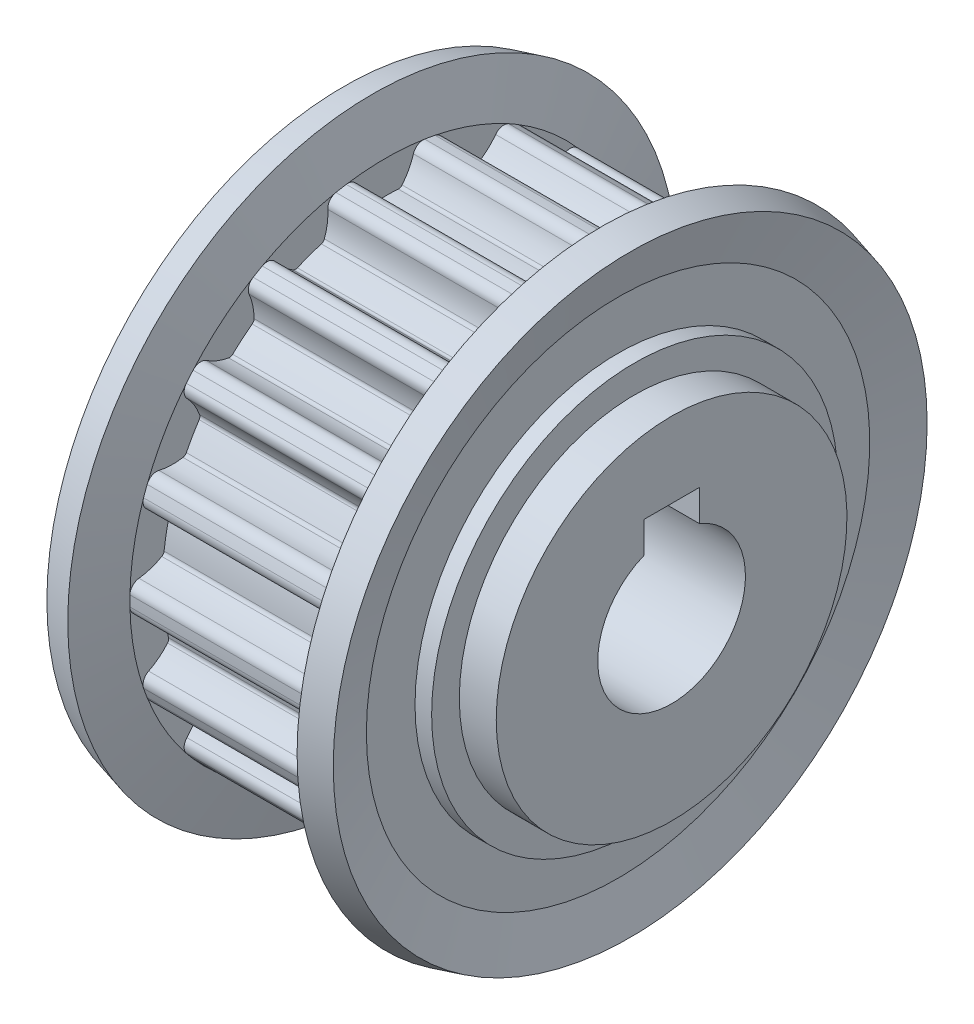
SolidWorks part; units mm, degrees
material "AISI 1045 강, 냉간압연"
ref_plane "정면" through (0, 0, 0) normal (0, 0, 1) x (1, 0, 0)
ref_plane "윗면" through (0, 0, 0) normal (0, 1, 0) x (1, 0, 0)
ref_plane "우측면" through (0, 0, 0) normal (1, 0, 0) x (0, 0, -1)
ref_plane "평면1" through (0, 0, 0) normal (0, 0, 1) x (1, 0, 0)
sketch "스케치1" plane through (0, 0, 0) normal (0, 0, 1) x (1, 0, 0)
  line L0 (0, 0) -> (0, 11)
  line L1 (0, 11) -> (0.9, 11)
  line L2 (0.9, 11) -> (0.9, 13.6344)
  line L3 (0.9, 13.6344) -> (0.2431, 16.0859)
  line L4 (0.2431, 16.0859) -> (1.7886, 16.5)
  line L5 (1.7886, 16.5) -> (2.5, 13.845)
  line L6 (2.5, 13.845) -> (13.5, 13.845)
  line L7 (13.5, 13.845) -> (14.2114, 16.5)
  line L8 (14.2114, 16.5) -> (15.7569, 16.0859)
  line L9 (15.7569, 16.0859) -> (15.1, 13.6344)
  line L10 (15.1, 13.6344) -> (15.1, 11)
  line L11 (15.1, 11) -> (16, 11)
  line L12 (16, 11) -> (16, 9.5)
  line L13 (16, 9.5) -> (25, 9.5)
  line L14 (25, 9.5) -> (25, 0)
  line L15 (25, 0) -> (0, 0)
  line L16 (25, 0) -> (0, 0) construction
revolve "회전1" add sketch "스케치1" angle 360 about L16
ref_plane "평면2" through (0, 0, 0) normal (0, 0, 1) x (1, 0, 0)
sketch "스케치2" plane through (0, 0, 0) normal (0, 0, 1) x (1, 0, 0)
  line L0 (0, 0) -> (0, 4)
  line L1 (0, 4) -> (25, 4)
  line L2 (25, 4) -> (25, 0)
  line L3 (25, 0) -> (0, 0)
  line L4 (25, 0) -> (0, 0) construction
revolve "컷-회전1" cut sketch "스케치2" angle 360 about L4
ref_plane "평면3" through (2.5, 0, 0) normal (1, 0, 0) x (0, 0, -1)
sketch "스케치3" plane through (2.5, 0, 0) normal (1, 0, 0) x (0, 0, -1)
  line L0 (2.1243, 13.6811) -> (2.1243, 14.1666)
  line L1 (-2.1243, 14.1666) -> (-2.1243, 13.6811)
  arc A0 (-2.1243, 13.6811) -> (-1.5129, 13.295) centre (-2.0399, 13.1376) cw
  arc A1 (-1.5129, 13.295) -> (-0.8988, 12.1454) centre (1.625, 14.2325) ccw
  arc A2 (-0.8988, 12.1454) -> (-0.6918, 12.0552) centre (-0.7062, 12.3048) ccw
  arc A3 (-0.6918, 12.0552) -> (0.6918, 12.0552) centre (0, 0) cw
  arc A4 (0.6918, 12.0552) -> (0.8988, 12.1454) centre (0.7062, 12.3048) ccw
  arc A5 (0.8988, 12.1454) -> (1.5129, 13.295) centre (-1.625, 14.2325) ccw
  arc A6 (1.5129, 13.295) -> (2.1243, 13.6811) centre (2.0399, 13.1376) cw
  arc A7 (2.1243, 14.1666) -> (-2.1243, 14.1666) centre (0, 0) ccw
extrude "컷-돌출1" cut sketch "스케치3" along normal blind 11
ref_plane "평면4" through (2.5, 0, 0) normal (1, 0, 0) x (0, 0, -1)
sketch "스케치4" plane through (2.5, 0, 0) normal (1, 0, 0) x (0, 0, -1)
  line L0 (6.6754, 12.1294) -> (6.8415, 12.5857)
  line L1 (2.8491, 14.0388) -> (2.683, 13.5825)
  arc A0 (2.683, 13.5825) -> (3.1255, 13.0107) centre (2.5764, 13.043) cw
  arc A1 (3.1255, 13.0107) -> (3.3094, 11.7204) centre (6.3948, 12.8184) ccw
  arc A2 (3.3094, 11.7204) -> (3.473, 11.5648) centre (3.5449, 11.8042) ccw
  arc A3 (3.473, 11.5648) -> (4.7732, 11.0915) centre (0, 0) cw
  arc A4 (4.7732, 11.0915) -> (4.9986, 11.1056) centre (4.872, 11.3212) ccw
  arc A5 (4.9986, 11.1056) -> (5.9689, 11.9758) centre (3.3408, 13.93) ccw
  arc A6 (5.9689, 11.9758) -> (6.6754, 12.1294) centre (6.4102, 11.6476) cw
  arc A7 (6.8415, 12.5857) -> (2.8491, 14.0388) centre (0, 0) ccw
extrude "컷-돌출2" cut sketch "스케치4" along normal blind 11
ref_plane "평면5" through (2.5, 0, 0) normal (1, 0, 0) x (0, 0, -1)
sketch "스케치5" plane through (2.5, 0, 0) normal (1, 0, 0) x (0, 0, -1)
  line L0 (10.4213, 9.1148) -> (10.7334, 9.4868)
  line L1 (7.4788, 12.2177) -> (7.1667, 11.8458)
  arc A0 (7.1667, 11.8458) -> (7.3869, 11.1571) centre (6.882, 11.3752) cw
  arc A1 (7.3869, 11.1571) -> (7.1184, 9.8817) centre (10.3933, 9.8582) ccw
  arc A2 (7.1184, 9.8817) -> (7.2189, 9.6795) centre (7.3684, 9.8799) ccw
  arc A3 (7.2189, 9.6795) -> (8.2789, 8.7901) centre (0, 0) cw
  arc A4 (8.2789, 8.7901) -> (8.4955, 8.7262) centre (8.4503, 8.9721) ccw
  arc A5 (8.4955, 8.7262) -> (9.7049, 9.2121) centre (7.9037, 11.9473) ccw
  arc A6 (9.7049, 9.2121) -> (10.4213, 9.1148) centre (10.0073, 8.7527) cw
  arc A7 (10.7334, 9.4868) -> (7.4788, 12.2177) centre (0, 0) ccw
extrude "컷-돌출3" cut sketch "스케치5" along normal blind 11
ref_plane "평면6" through (2.5, 0, 0) normal (1, 0, 0) x (0, 0, -1)
sketch "스케치6" plane through (2.5, 0, 0) normal (1, 0, 0) x (0, 0, -1)
  line L0 (12.9103, 5.0008) -> (13.3308, 5.2436)
  line L1 (11.2065, 8.923) -> (10.786, 8.6802)
  arc A0 (10.786, 8.6802) -> (10.7573, 7.9578) centre (10.3575, 8.3354) cw
  arc A1 (10.7573, 7.9578) -> (10.0688, 6.8511) centre (13.1382, 5.709) ccw
  arc A2 (10.0688, 6.8511) -> (10.0942, 6.6267) centre (10.3032, 6.7639) ccw
  arc A3 (10.0942, 6.6267) -> (10.786, 5.4284) centre (0, 0) cw
  arc A4 (10.786, 5.4284) -> (10.9677, 5.2943) centre (11.0093, 5.5408) ccw
  arc A5 (10.9677, 5.2943) -> (12.2703, 5.3373) centre (11.5132, 8.5236) ccw
  arc A6 (12.2703, 5.3373) -> (12.9103, 5.0008) centre (12.3974, 4.8022) cw
  arc A7 (13.3308, 5.2436) -> (11.2065, 8.923) centre (0, 0) ccw
extrude "컷-돌출4" cut sketch "스케치6" along normal blind 11
ref_plane "평면7" through (2.5, 0, 0) normal (1, 0, 0) x (0, 0, -1)
sketch "스케치7" plane through (2.5, 0, 0) normal (1, 0, 0) x (0, 0, -1)
  line L0 (13.8421, 0.2836) -> (14.3203, 0.368)
  line L1 (13.5825, 4.552) -> (13.1043, 4.4677)
  arc A0 (13.1043, 4.4677) -> (12.8303, 3.7986) centre (12.5838, 4.2902) cw
  arc A1 (12.8303, 3.7986) -> (11.8048, 2.9942) centre (14.2985, 0.8711) ccw
  arc A2 (11.8048, 2.9942) -> (11.7519, 2.7747) centre (11.9952, 2.8321) ccw
  arc A3 (11.7519, 2.7747) -> (11.9922, 1.412) centre (0, 0) cw
  arc A4 (11.9922, 1.412) -> (12.117, 1.2239) centre (12.2404, 1.4413) ccw
  arc A5 (12.117, 1.2239) -> (13.3558, 0.8187) centre (13.7341, 4.0718) ccw
  arc A6 (13.3558, 0.8187) -> (13.8421, 0.2836) centre (13.2922, 0.2724) cw
  arc A7 (14.3203, 0.368) -> (13.5825, 4.552) centre (0, 0) ccw
extrude "컷-돌출5" cut sketch "스케치7" along normal blind 11
ref_plane "평면8" through (2.5, 0, 0) normal (1, 0, 0) x (0, 0, -1)
sketch "스케치8" plane through (2.5, 0, 0) normal (1, 0, 0) x (0, 0, -1)
  line L0 (13.1043, -4.4677) -> (13.5825, -4.552)
  line L1 (14.3203, -0.368) -> (13.8421, -0.2836)
  arc A0 (13.8421, -0.2836) -> (13.3558, -0.8187) centre (13.2922, -0.2724) cw
  arc A1 (13.3558, -0.8187) -> (12.117, -1.2239) centre (13.7341, -4.0718) ccw
  arc A2 (12.117, -1.2239) -> (11.9922, -1.412) centre (12.2404, -1.4413) ccw
  arc A3 (11.9922, -1.412) -> (11.7519, -2.7747) centre (0, 0) cw
  arc A4 (11.7519, -2.7747) -> (11.8048, -2.9942) centre (11.9952, -2.8321) ccw
  arc A5 (11.8048, -2.9942) -> (12.8303, -3.7986) centre (14.2985, -0.8711) ccw
  arc A6 (12.8303, -3.7986) -> (13.1043, -4.4677) centre (12.5838, -4.2902) cw
  arc A7 (13.5825, -4.552) -> (14.3203, -0.368) centre (0, 0) ccw
extrude "컷-돌출6" cut sketch "스케치8" along normal blind 11
ref_plane "평면9" through (2.5, 0, 0) normal (1, 0, 0) x (0, 0, -1)
sketch "스케치9" plane through (2.5, 0, 0) normal (1, 0, 0) x (0, 0, -1)
  line L0 (10.786, -8.6802) -> (11.2065, -8.923)
  line L1 (13.3308, -5.2436) -> (12.9103, -5.0008)
  arc A0 (12.9103, -5.0008) -> (12.2703, -5.3373) centre (12.3974, -4.8022) cw
  arc A1 (12.2703, -5.3373) -> (10.9677, -5.2943) centre (11.5132, -8.5236) ccw
  arc A2 (10.9677, -5.2943) -> (10.786, -5.4284) centre (11.0093, -5.5408) ccw
  arc A3 (10.786, -5.4284) -> (10.0942, -6.6267) centre (0, 0) cw
  arc A4 (10.0942, -6.6267) -> (10.0688, -6.8511) centre (10.3032, -6.7639) ccw
  arc A5 (10.0688, -6.8511) -> (10.7573, -7.9578) centre (13.1382, -5.709) ccw
  arc A6 (10.7573, -7.9578) -> (10.786, -8.6802) centre (10.3575, -8.3354) cw
  arc A7 (11.2065, -8.923) -> (13.3308, -5.2436) centre (0, 0) ccw
extrude "컷-돌출7" cut sketch "스케치9" along normal blind 11
ref_plane "평면10" through (2.5, 0, 0) normal (1, 0, 0) x (0, 0, -1)
sketch "스케치10" plane through (2.5, 0, 0) normal (1, 0, 0) x (0, 0, -1)
  line L0 (7.1667, -11.8458) -> (7.4788, -12.2177)
  line L1 (10.7334, -9.4868) -> (10.4213, -9.1148)
  arc A0 (10.4213, -9.1148) -> (9.7049, -9.2121) centre (10.0073, -8.7527) cw
  arc A1 (9.7049, -9.2121) -> (8.4955, -8.7262) centre (7.9037, -11.9473) ccw
  arc A2 (8.4955, -8.7262) -> (8.2789, -8.7901) centre (8.4503, -8.9721) ccw
  arc A3 (8.2789, -8.7901) -> (7.2189, -9.6795) centre (0, 0) cw
  arc A4 (7.2189, -9.6795) -> (7.1184, -9.8817) centre (7.3684, -9.8799) ccw
  arc A5 (7.1184, -9.8817) -> (7.3869, -11.1571) centre (10.3933, -9.8582) ccw
  arc A6 (7.3869, -11.1571) -> (7.1667, -11.8458) centre (6.882, -11.3752) cw
  arc A7 (7.4788, -12.2177) -> (10.7334, -9.4868) centre (0, 0) ccw
extrude "컷-돌출8" cut sketch "스케치10" along normal blind 11
ref_plane "평면11" through (2.5, 0, 0) normal (1, 0, 0) x (0, 0, -1)
sketch "스케치11" plane through (2.5, 0, 0) normal (1, 0, 0) x (0, 0, -1)
  line L0 (2.683, -13.5825) -> (2.8491, -14.0388)
  line L1 (6.8415, -12.5857) -> (6.6754, -12.1294)
  arc A0 (6.6754, -12.1294) -> (5.9689, -11.9758) centre (6.4102, -11.6476) cw
  arc A1 (5.9689, -11.9758) -> (4.9986, -11.1056) centre (3.3408, -13.93) ccw
  arc A2 (4.9986, -11.1056) -> (4.7732, -11.0915) centre (4.872, -11.3212) ccw
  arc A3 (4.7732, -11.0915) -> (3.473, -11.5648) centre (0, 0) cw
  arc A4 (3.473, -11.5648) -> (3.3094, -11.7204) centre (3.5449, -11.8042) ccw
  arc A5 (3.3094, -11.7204) -> (3.1255, -13.0107) centre (6.3948, -12.8184) ccw
  arc A6 (3.1255, -13.0107) -> (2.683, -13.5825) centre (2.5764, -13.043) cw
  arc A7 (2.8491, -14.0388) -> (6.8415, -12.5857) centre (0, 0) ccw
extrude "컷-돌출9" cut sketch "스케치11" along normal blind 11
ref_plane "평면12" through (2.5, 0, 0) normal (1, 0, 0) x (0, 0, -1)
sketch "스케치12" plane through (2.5, 0, 0) normal (1, 0, 0) x (0, 0, -1)
  line L0 (-2.1243, -13.6811) -> (-2.1243, -14.1666)
  line L1 (2.1243, -14.1666) -> (2.1243, -13.6811)
  arc A0 (2.1243, -13.6811) -> (1.5129, -13.295) centre (2.0399, -13.1376) cw
  arc A1 (1.5129, -13.295) -> (0.8988, -12.1454) centre (-1.625, -14.2325) ccw
  arc A2 (0.8988, -12.1454) -> (0.6918, -12.0552) centre (0.7062, -12.3048) ccw
  arc A3 (0.6918, -12.0552) -> (-0.6918, -12.0552) centre (0, 0) cw
  arc A4 (-0.6918, -12.0552) -> (-0.8988, -12.1454) centre (-0.7062, -12.3048) ccw
  arc A5 (-0.8988, -12.1454) -> (-1.5129, -13.295) centre (1.625, -14.2325) ccw
  arc A6 (-1.5129, -13.295) -> (-2.1243, -13.6811) centre (-2.0399, -13.1376) cw
  arc A7 (-2.1243, -14.1666) -> (2.1243, -14.1666) centre (0, 0) ccw
extrude "컷-돌출10" cut sketch "스케치12" along normal blind 11
ref_plane "평면13" through (2.5, 0, 0) normal (1, 0, 0) x (0, 0, -1)
sketch "스케치13" plane through (2.5, 0, 0) normal (1, 0, 0) x (0, 0, -1)
  line L0 (-6.6754, -12.1294) -> (-6.8415, -12.5857)
  line L1 (-2.8491, -14.0388) -> (-2.683, -13.5825)
  arc A0 (-2.683, -13.5825) -> (-3.1255, -13.0107) centre (-2.5764, -13.043) cw
  arc A1 (-3.1255, -13.0107) -> (-3.3094, -11.7204) centre (-6.3948, -12.8184) ccw
  arc A2 (-3.3094, -11.7204) -> (-3.473, -11.5648) centre (-3.5449, -11.8042) ccw
  arc A3 (-3.473, -11.5648) -> (-4.7732, -11.0915) centre (0, 0) cw
  arc A4 (-4.7732, -11.0915) -> (-4.9986, -11.1056) centre (-4.872, -11.3212) ccw
  arc A5 (-4.9986, -11.1056) -> (-5.9689, -11.9758) centre (-3.3408, -13.93) ccw
  arc A6 (-5.9689, -11.9758) -> (-6.6754, -12.1294) centre (-6.4102, -11.6476) cw
  arc A7 (-6.8415, -12.5857) -> (-2.8491, -14.0388) centre (0, 0) ccw
extrude "컷-돌출11" cut sketch "스케치13" along normal blind 11
ref_plane "평면14" through (2.5, 0, 0) normal (1, 0, 0) x (0, 0, -1)
sketch "스케치14" plane through (2.5, 0, 0) normal (1, 0, 0) x (0, 0, -1)
  line L0 (-10.4213, -9.1148) -> (-10.7334, -9.4868)
  line L1 (-7.4788, -12.2177) -> (-7.1667, -11.8458)
  arc A0 (-7.1667, -11.8458) -> (-7.3869, -11.1571) centre (-6.882, -11.3752) cw
  arc A1 (-7.3869, -11.1571) -> (-7.1184, -9.8817) centre (-10.3933, -9.8582) ccw
  arc A2 (-7.1184, -9.8817) -> (-7.2189, -9.6795) centre (-7.3684, -9.8799) ccw
  arc A3 (-7.2189, -9.6795) -> (-8.2789, -8.7901) centre (0, 0) cw
  arc A4 (-8.2789, -8.7901) -> (-8.4955, -8.7262) centre (-8.4503, -8.9721) ccw
  arc A5 (-8.4955, -8.7262) -> (-9.7049, -9.2121) centre (-7.9037, -11.9473) ccw
  arc A6 (-9.7049, -9.2121) -> (-10.4213, -9.1148) centre (-10.0073, -8.7527) cw
  arc A7 (-10.7334, -9.4868) -> (-7.4788, -12.2177) centre (0, 0) ccw
extrude "컷-돌출12" cut sketch "스케치14" along normal blind 11
ref_plane "평면15" through (2.5, 0, 0) normal (1, 0, 0) x (0, 0, -1)
sketch "스케치15" plane through (2.5, 0, 0) normal (1, 0, 0) x (0, 0, -1)
  line L0 (-12.9103, -5.0008) -> (-13.3308, -5.2436)
  line L1 (-11.2065, -8.923) -> (-10.786, -8.6802)
  arc A0 (-10.786, -8.6802) -> (-10.7573, -7.9578) centre (-10.3575, -8.3354) cw
  arc A1 (-10.7573, -7.9578) -> (-10.0688, -6.8511) centre (-13.1382, -5.709) ccw
  arc A2 (-10.0688, -6.8511) -> (-10.0942, -6.6267) centre (-10.3032, -6.7639) ccw
  arc A3 (-10.0942, -6.6267) -> (-10.786, -5.4284) centre (0, 0) cw
  arc A4 (-10.786, -5.4284) -> (-10.9677, -5.2943) centre (-11.0093, -5.5408) ccw
  arc A5 (-10.9677, -5.2943) -> (-12.2703, -5.3373) centre (-11.5132, -8.5236) ccw
  arc A6 (-12.2703, -5.3373) -> (-12.9103, -5.0008) centre (-12.3974, -4.8022) cw
  arc A7 (-13.3308, -5.2436) -> (-11.2065, -8.923) centre (0, 0) ccw
extrude "컷-돌출13" cut sketch "스케치15" along normal blind 11
ref_plane "평면16" through (2.5, 0, 0) normal (1, 0, 0) x (0, 0, -1)
sketch "스케치16" plane through (2.5, 0, 0) normal (1, 0, 0) x (0, 0, -1)
  line L0 (-13.8421, -0.2836) -> (-14.3203, -0.368)
  line L1 (-13.5825, -4.552) -> (-13.1043, -4.4677)
  arc A0 (-13.1043, -4.4677) -> (-12.8303, -3.7986) centre (-12.5838, -4.2902) cw
  arc A1 (-12.8303, -3.7986) -> (-11.8048, -2.9942) centre (-14.2985, -0.8711) ccw
  arc A2 (-11.8048, -2.9942) -> (-11.7519, -2.7747) centre (-11.9952, -2.8321) ccw
  arc A3 (-11.7519, -2.7747) -> (-11.9922, -1.412) centre (0, 0) cw
  arc A4 (-11.9922, -1.412) -> (-12.117, -1.2239) centre (-12.2404, -1.4413) ccw
  arc A5 (-12.117, -1.2239) -> (-13.3558, -0.8187) centre (-13.7341, -4.0718) ccw
  arc A6 (-13.3558, -0.8187) -> (-13.8421, -0.2836) centre (-13.2922, -0.2724) cw
  arc A7 (-14.3203, -0.368) -> (-13.5825, -4.552) centre (0, 0) ccw
extrude "컷-돌출14" cut sketch "스케치16" along normal blind 11
ref_plane "평면17" through (2.5, 0, 0) normal (1, 0, 0) x (0, 0, -1)
sketch "스케치17" plane through (2.5, 0, 0) normal (1, 0, 0) x (0, 0, -1)
  line L0 (-13.1043, 4.4677) -> (-13.5825, 4.552)
  line L1 (-14.3203, 0.368) -> (-13.8421, 0.2836)
  arc A0 (-13.8421, 0.2836) -> (-13.3558, 0.8187) centre (-13.2922, 0.2724) cw
  arc A1 (-13.3558, 0.8187) -> (-12.117, 1.2239) centre (-13.7341, 4.0718) ccw
  arc A2 (-12.117, 1.2239) -> (-11.9922, 1.412) centre (-12.2404, 1.4413) ccw
  arc A3 (-11.9922, 1.412) -> (-11.7519, 2.7747) centre (0, 0) cw
  arc A4 (-11.7519, 2.7747) -> (-11.8048, 2.9942) centre (-11.9952, 2.8321) ccw
  arc A5 (-11.8048, 2.9942) -> (-12.8303, 3.7986) centre (-14.2985, 0.8711) ccw
  arc A6 (-12.8303, 3.7986) -> (-13.1043, 4.4677) centre (-12.5838, 4.2902) cw
  arc A7 (-13.5825, 4.552) -> (-14.3203, 0.368) centre (0, 0) ccw
extrude "컷-돌출15" cut sketch "스케치17" along normal blind 11
ref_plane "평면18" through (2.5, 0, 0) normal (1, 0, 0) x (0, 0, -1)
sketch "스케치18" plane through (2.5, 0, 0) normal (1, 0, 0) x (0, 0, -1)
  line L0 (-10.786, 8.6802) -> (-11.2065, 8.923)
  line L1 (-13.3308, 5.2436) -> (-12.9103, 5.0008)
  arc A0 (-12.9103, 5.0008) -> (-12.2703, 5.3373) centre (-12.3974, 4.8022) cw
  arc A1 (-12.2703, 5.3373) -> (-10.9677, 5.2943) centre (-11.5132, 8.5236) ccw
  arc A2 (-10.9677, 5.2943) -> (-10.786, 5.4284) centre (-11.0093, 5.5408) ccw
  arc A3 (-10.786, 5.4284) -> (-10.0942, 6.6267) centre (0, 0) cw
  arc A4 (-10.0942, 6.6267) -> (-10.0688, 6.8511) centre (-10.3032, 6.7639) ccw
  arc A5 (-10.0688, 6.8511) -> (-10.7573, 7.9578) centre (-13.1382, 5.709) ccw
  arc A6 (-10.7573, 7.9578) -> (-10.786, 8.6802) centre (-10.3575, 8.3354) cw
  arc A7 (-11.2065, 8.923) -> (-13.3308, 5.2436) centre (0, 0) ccw
extrude "컷-돌출16" cut sketch "스케치18" along normal blind 11
ref_plane "평면19" through (2.5, 0, 0) normal (1, 0, 0) x (0, 0, -1)
sketch "스케치19" plane through (2.5, 0, 0) normal (1, 0, 0) x (0, 0, -1)
  line L0 (-7.1667, 11.8458) -> (-7.4788, 12.2177)
  line L1 (-10.7334, 9.4868) -> (-10.4213, 9.1148)
  arc A0 (-10.4213, 9.1148) -> (-9.7049, 9.2121) centre (-10.0073, 8.7527) cw
  arc A1 (-9.7049, 9.2121) -> (-8.4955, 8.7262) centre (-7.9037, 11.9473) ccw
  arc A2 (-8.4955, 8.7262) -> (-8.2789, 8.7901) centre (-8.4503, 8.9721) ccw
  arc A3 (-8.2789, 8.7901) -> (-7.2189, 9.6795) centre (0, 0) cw
  arc A4 (-7.2189, 9.6795) -> (-7.1184, 9.8817) centre (-7.3684, 9.8799) ccw
  arc A5 (-7.1184, 9.8817) -> (-7.3869, 11.1571) centre (-10.3933, 9.8582) ccw
  arc A6 (-7.3869, 11.1571) -> (-7.1667, 11.8458) centre (-6.882, 11.3752) cw
  arc A7 (-7.4788, 12.2177) -> (-10.7334, 9.4868) centre (0, 0) ccw
extrude "컷-돌출17" cut sketch "스케치19" along normal blind 11
ref_plane "평면20" through (2.5, 0, 0) normal (1, 0, 0) x (0, 0, -1)
sketch "스케치20" plane through (2.5, 0, 0) normal (1, 0, 0) x (0, 0, -1)
  line L0 (-2.683, 13.5825) -> (-2.8491, 14.0388)
  line L1 (-6.8415, 12.5857) -> (-6.6754, 12.1294)
  arc A0 (-6.6754, 12.1294) -> (-5.9689, 11.9758) centre (-6.4102, 11.6476) cw
  arc A1 (-5.9689, 11.9758) -> (-4.9986, 11.1056) centre (-3.3408, 13.93) ccw
  arc A2 (-4.9986, 11.1056) -> (-4.7732, 11.0915) centre (-4.872, 11.3212) ccw
  arc A3 (-4.7732, 11.0915) -> (-3.473, 11.5648) centre (0, 0) cw
  arc A4 (-3.473, 11.5648) -> (-3.3094, 11.7204) centre (-3.5449, 11.8042) ccw
  arc A5 (-3.3094, 11.7204) -> (-3.1255, 13.0107) centre (-6.3948, 12.8184) ccw
  arc A6 (-3.1255, 13.0107) -> (-2.683, 13.5825) centre (-2.5764, 13.043) cw
  arc A7 (-2.8491, 14.0388) -> (-6.8415, 12.5857) centre (0, 0) ccw
extrude "컷-돌출18" cut sketch "스케치20" along normal blind 11
ref_plane "평면21" through (0, 0, 0) normal (1, 0, 0) x (0, 0, -1)
sketch "스케치21" plane through (0, 0, 0) normal (1, 0, 0) x (0, 0, -1)
  line L0 (-1.5, 5.4) -> (-1.5, 0)
  line L1 (-1.5, 0) -> (1.5, 0)
  line L2 (1.5, 0) -> (1.5, 5.4)
  line L3 (1.5, 5.4) -> (-1.5, 5.4)
extrude "컷-돌출19" cut sketch "스케치21" along normal blind 25
ref_plane "평면22" through (20.5, 0, 0) normal (1, 0, 0) x (0, 0, -1)
sketch "스케치22" plane through (20.5, 0, 0) normal (1, 0, 0) x (0, 0, -1)
  line L0 (0, 9.5) -> (1.621, 9.5)
  line L1 (1.621, 9.5) -> (1.621, 0)
  line L2 (1.621, 0) -> (0, 0)
  line L3 (0, 0) -> (0, 9.5)
  line L4 (0, 0) -> (0, 9.5) construction
revolve "컷-회전2" cut sketch "스케치22" angle 360 about L4
ref_plane "평면23" through (20.5, 0, 0) normal (1, 0, 0) x (0, 0, -1)
sketch "스케치23" plane through (20.5, 0, 0) normal (1, 0, 0) x (0, 0, -1)
  line L0 (8.2272, -4.75) -> (7.4167, -6.1538)
  line L1 (7.4167, -6.1538) -> (-0.8105, -1.4038)
  line L2 (-0.8105, -1.4038) -> (0, 0)
  line L3 (0, 0) -> (8.2272, -4.75)
  line L4 (0, 0) -> (8.2272, -4.75) construction
revolve "컷-회전3" cut sketch "스케치23" angle 360 about L4
sketch "스케치24" plane through (0, 0, 0) normal (0, 0, 1) x (1, 0, 0)
  line L0 (0, 11) -> (0, -11) construction
  line L1 (25, 9.5) -> (18, 9.5)
  line L2 (25, 9.5) -> (25, 0)
  line L3 (25, 0) -> (18, 0)
  line L4 (18, 9.5) -> (18, 0)
  dimension "D1" = 18
revolve "컷-회전4" cut sketch "스케치24" angle 360 about L3
